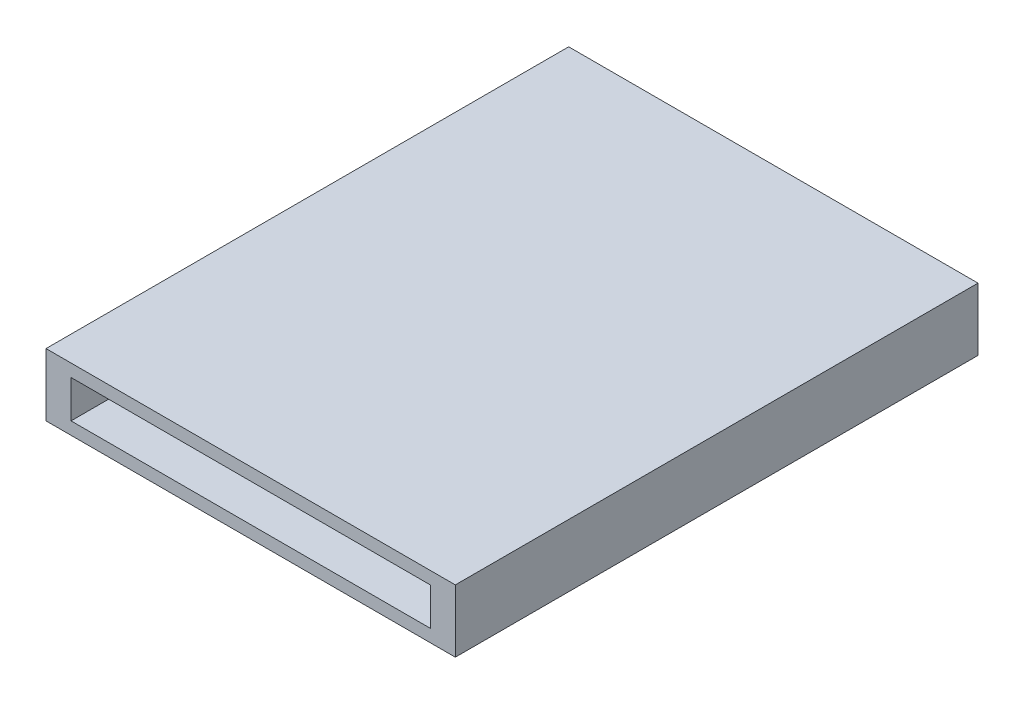
SolidWorks part; units mm, degrees
ref_plane "Front Plane" through (0, 0, 0) normal (0, 0, 1) x (1, 0, 0)
ref_plane "Top Plane" through (0, 0, 0) normal (0, 1, 0) x (1, 0, 0)
ref_plane "Right Plane" through (0, 0, 0) normal (1, 0, 0) x (0, 0, -1)
sketch "Sketch1" plane through (0, 0, 0) normal (0, 1, 0) x (1, 0, 0)
  line L0 (-56.8223, 30.2863) -> (-56.8223, 9.4252)
  line L1 (-56.8223, 9.4252) -> (-40.4853, 9.4252)
  line L2 (-40.4853, 9.4252) -> (-40.4853, 30.2863)
  line L3 (-40.4853, 30.2863) -> (-56.8223, 30.2863)
extrude "Boss-Extrude1" add sketch "Sketch1" along normal blind 2.5
sketch "Sketch2" plane through (0, 0, -9.4252) normal (0, 0, 1) x (1, 0, 0)
  line L6 (-55.8223, 0.5) -> (-55.8223, 2)
  line L11 (-55.8223, 2) -> (-41.4853, 2)
  line L12 (-41.4853, 2) -> (-41.4853, 0.5)
  line L13 (-41.4853, 0.5) -> (-55.8223, 0.5)
extrude "Cut-Extrude1" cut sketch "Sketch2" against normal blind 20.7 contours L12 L13 L6 L11
